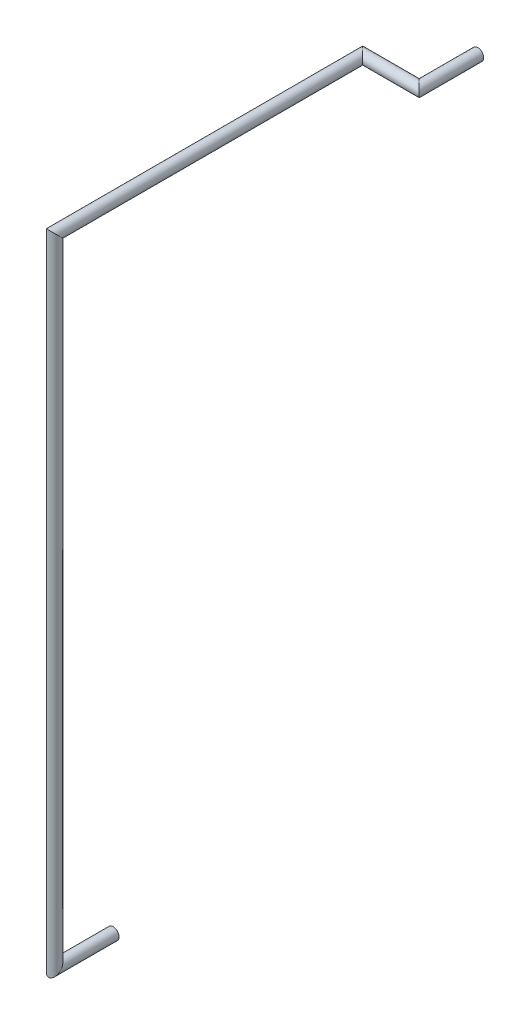
SolidWorks part; units mm, degrees
ref_plane "Plan de face" through (0, 0, 0) normal (1, 0, 0) x (0, 1, 0)
ref_plane "Plan de dessus" through (0, 0, 0) normal (0, 0, 1) x (0, 1, 0)
ref_plane "Plan de droite" through (0, 0, 0) normal (0, 1, 0) x (-1, 0, 0)
sketch3d "Esquisse3D1"
  line L0 (0, 0, 0) -> (0, 0, 5)
  line L1 (0, 0, 5) -> (0, 54.22, 5)
  line L2 (0, 54.22, 5) -> (0, 54.22, -21.29)
  line L3 (0, 54.22, -21.29) -> (4.82, 54.22, -21.29)
  line L4 (4.82, 54.22, -21.29) -> (4.82, 54.22, -26.29)
  dimension "D1" = 5
  dimension "D2" = 5
  dimension "D3" = 4.82
  dimension "D4" = 26.29
  dimension "D5" = 54.22
sketch "Esquisse1" plane through (0, 0, 0) normal (0, 0, 1) x (0, 1, 0)
  circle A0 centre (0, 0) radius 0.5
  dimension "D1" = 1
sweep "Balayage1" add profiles "Esquisse1" path "Esquisse3D1"
